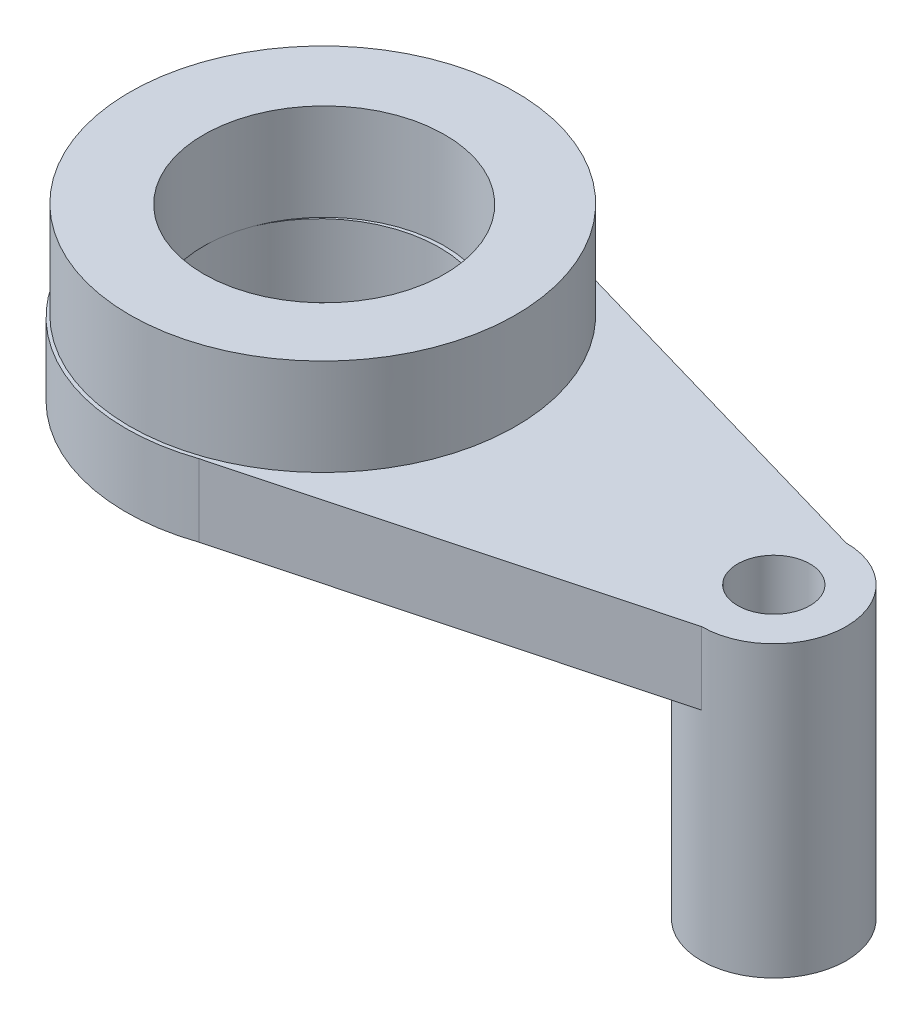
SolidWorks part; units mm, degrees
material "Galvanized Steel"
ref_plane "Front Plane" through (0, 0, 0) normal (0, 0, 1) x (1, 0, 0)
ref_plane "Top Plane" through (0, 0, 0) normal (0, 1, 0) x (1, 0, 0)
ref_plane "Right Plane" through (0, 0, 0) normal (1, 0, 0) x (0, 0, -1)
sketch "Sketch2" plane through (0, 0, 0) normal (0, 1, 0) x (1, 0, 0)
  line L0 (37945.7392, -6672.5044) -> (5073.2921, -15446.9598)
  line L1 (37945.6012, 5327.0061) -> (4453.5287, 15017.9602)
  line L2 (5073.2921, -15446.9598) -> (5072.8682, -15445.8892)
  line L3 (4453.5287, 15017.9602) -> (4453.1547, 15016.6675)
  line L4 (37945.6012, 5327.0061) -> (37945.6012, 5326.5019)
  circle A0 centre (-121.9, -313.8841) radius 10000
  circle A1 centre (-121.9, -313.8841) radius 16000
  circle A2 centre (37945.6012, -672.9608) radius 3000
  circle A3 centre (37945.6012, -672.9608) radius 5999.9669
extrude "Boss-Extrude8" add sketch "Sketch2" along normal blind 6000 contours A3 L1 A1 L0 | A0 | A2
sketch "Sketch8" plane through (0, 6000, 0) normal (0, 1, 0) x (1, 0, 0)
  circle A0 centre (0, 0) radius 10000
  circle A1 centre (-121.9, 0) radius 16000
  circle A2 centre (37945.6012, -672.9608) radius 3000
  circle A3 centre (37945.6012, -672.9608) radius 5999.9669
extrude "Boss-Extrude9" add sketch "Sketch8" along normal blind 8000 contours A0 | A1
sketch "Sketch13" plane through (0, 6000, 0) normal (0, 1, 0) x (1, 0, 0)
  circle A0 centre (37945.6012, -672.9608) radius 5999.9669
  circle A2 centre (37945.6012, -672.9608) radius 3000
extrude "Boss-Extrude10" add sketch "Sketch13" against normal blind 24000
